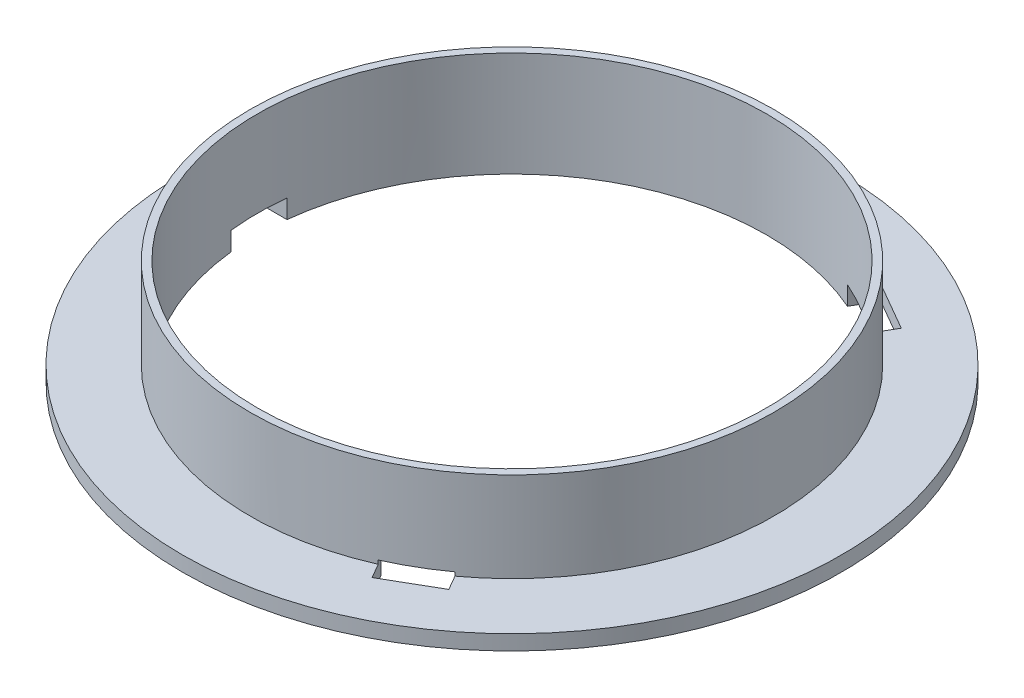
SolidWorks part; units mm, degrees
ref_plane "Front Plane" through (0, 0, 0) normal (0, 0, 1) x (1, 0, 0)
ref_plane "Top Plane" through (0, 0, 0) normal (0, 1, 0) x (1, 0, 0)
ref_plane "Right Plane" through (0, 0, 0) normal (1, 0, 0) x (0, 0, -1)
sketch "Sketch2" plane through (0, 0, 0) normal (1, 0, 0) x (0, 0, -1)
  line L0 (0, 0) -> (0, 42.9825) construction
  line L1 (0, 0) -> (34, 0) construction
  line L2 (34, 0) -> (44, 0)
  line L3 (44, 0) -> (44, 2)
  line L4 (44, 2) -> (35, 2)
  line L5 (35, 2) -> (35, 14)
  line L6 (35, 14) -> (34, 14)
  line L7 (34, 14) -> (34, 0)
  dimension "D1" = 34
  dimension "D2" = 10
  dimension "D3" = 2
  dimension "D4" = 12
  dimension "D5" = 1
revolve "Revolve1" add sketch "Sketch2" angle 360 about L0
sketch "Sketch5" plane through (0, 0, 0) normal (0, -1, 0) x (-1, 0, 0)
  line L0 (-15.2737, -33.9548) -> (-21.7689, -30.2048)
  line L1 (37.0426, 3.75) -> (33.7926, 3.75)
  line L2 (37.0426, 3.75) -> (37.0426, -3.75)
  line L3 (37.0426, -3.75) -> (33.7926, -3.75)
  line L4 (33.7926, 3.75) -> (33.7926, -3.75)
  line L5 (37.0426, 3.75) -> (33.7926, -3.75) construction
  line L6 (37.0426, -3.75) -> (33.7926, 3.75) construction
  line L7 (-15.2737, -33.9548) -> (-13.6487, -31.1402)
  line L8 (-13.6487, -31.1402) -> (-20.1439, -27.3902)
  line L9 (-21.7689, -30.2048) -> (-20.1439, -27.3902)
  line L10 (-21.7689, 30.2048) -> (-15.2737, 33.9548)
  line L11 (-21.7689, 30.2048) -> (-20.1439, 27.3902)
  line L12 (-20.1439, 27.3902) -> (-13.6487, 31.1402)
  line L13 (-15.2737, 33.9548) -> (-13.6487, 31.1402)
  line L14 (35.4176, 0) -> (0, 0) construction
  circle A0 centre (0, 0) radius 34 construction
  point P0 (35.4176, 0)
  point P9 (0, 0)
  point P18 (0, 0)
  dimension "D1" = 7.5
  dimension "D2" = 3.25
  dimension "D3" = 3
extrude "Cut-Extrude1" cut sketch "Sketch5" against normal blind 2.5
